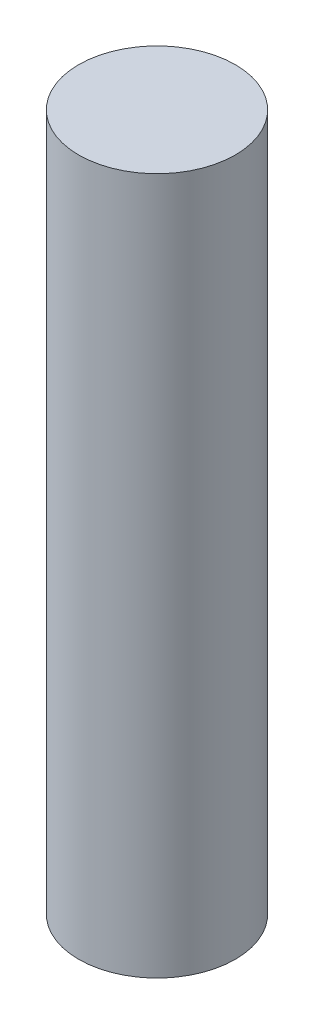
SolidWorks part; units mm, degrees
ref_plane "Front Plane" through (0, 0, 0) normal (0, 0, 1) x (1, 0, 0)
ref_plane "Top Plane" through (0, 0, 0) normal (0, 1, 0) x (1, 0, 0)
ref_plane "Right Plane" through (0, 0, 0) normal (1, 0, 0) x (0, 0, -1)
sketch "Sketch1" plane through (0, 0, 0) normal (0, 1, 0) x (1, 0, 0)
  circle A0 centre (0, 0) radius 12.7
  dimension "D1" = 25.4
extrude "Boss-Extrude1" add sketch "Sketch1" along normal blind 113
equation "\"carbon_fiber_tube_diam\"= 1in"
equation "\"clip_tube_diam\"= 6mm"
equation "\"middle_tube_len\"= 500mm"
equation "\"horizontal_pipe_spacing\"= 250mm"
equation "\"D1@Sketch1\"=\"carbon_fiber_tube_diam\""
